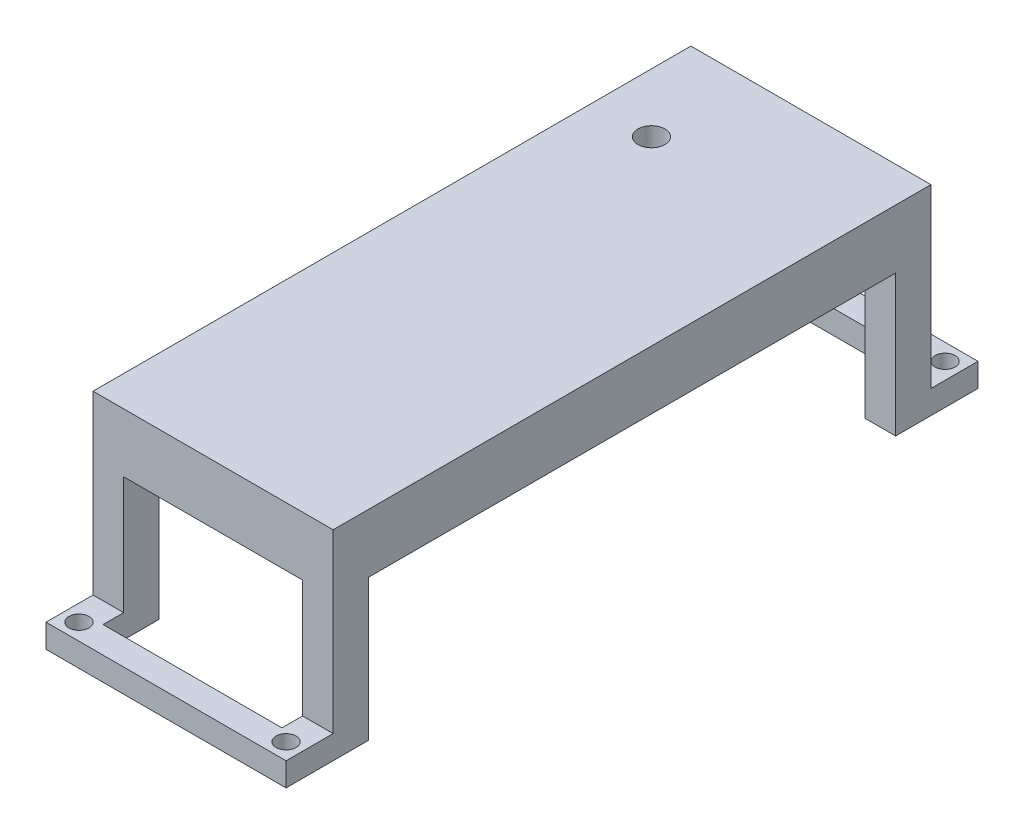
SolidWorks part; units mm, degrees
ref_plane "Front Plane" through (0, 0, 0) normal (0, 0, 1) x (1, 0, 0)
ref_plane "Top Plane" through (0, 0, 0) normal (0, 1, 0) x (1, 0, 0)
ref_plane "Right Plane" through (0, 0, 0) normal (1, 0, 0) x (0, 0, -1)
sketch "Sketch1" plane through (0, 0, 0) normal (0, 1, 0) x (1, 0, 0)
  line L0 (-55, 0) -> (55, 0) construction
  line L1 (-51, 11.25) -> (51, 11.25)
  line L3 (-38, 0) -> (38, 0)
  line L4 (51, 11.25) -> (51, 0)
  line L8 (-51, -13.75) -> (-38, -13.75)
  line L9 (-38, -13.75) -> (-38, 0)
  line L10 (0, -55) -> (0, 55) construction
  line L11 (51, -13.75) -> (38, -13.75)
  line L12 (38, -13.75) -> (38, 0)
  line L13 (51, 0) -> (51, -13.75)
  line L14 (-44, 4.25) -> (-44, 11.25) construction
  line L15 (-44, 4.25) -> (-51, 4.25) construction
  line L19 (-51, 11.25) -> (-51, -13.75)
  circle A0 centre (-44, 4.25) radius 4.25
  circle A1 centre (44, 4.25) radius 4.25
  point P6 (0, 0)
  dimension "D2" = 8.5
  dimension "D1" = 102
  dimension "D3" = 76
  dimension "D4" = 25
  dimension "D5" = 7
extrude "Boss-Extrude1" add sketch "Sketch1" along normal blind 10
sketch "Sketch2" plane through (0, 0, 13.75) normal (0, 0, 1) x (1, 0, 0)
  line L0 (-51, 0) -> (-51, 85)
  line L1 (-51, 10) -> (-51, 0) construction
  line L2 (-51, 85) -> (51, 85)
  line L3 (51, 85) -> (51, 0)
  line L4 (51, 10) -> (51, 0) construction
  line L5 (-51, 0) -> (-38, 0)
  line L6 (-38, 0) -> (-38, 60)
  line L7 (-38, 60) -> (38, 60)
  line L8 (38, 60) -> (38, 0)
  line L9 (-15.9953, 60) -> (-15.9953, 85) construction
  line L10 (-38, 52.4694) -> (-51, 52.4694) construction
  line L11 (13.75, 0) -> (-13.75, 0) construction
  line L12 (38, 0) -> (51, 0)
  line L16 (38, 0) -> (51, 0)
  line L17 (51, 0) -> (51, 10)
  line L18 (51, 10) -> (38, 10)
  line L19 (38, 10) -> (38, 0)
  line L21 (51, 0) -> (51, 10)
  line L23 (38, 10) -> (38, 0)
  dimension "D1" = 60
  dimension "D2" = 25
  dimension "D3" = 0
extrude "Boss-Extrude2" add sketch "Sketch2" against normal blind 5 and the other way blind 10
sketch "Sketch3" plane through (0, 0, 23.75) normal (0, 0, 1) x (1, 0, 0)
  line L0 (51, 85) -> (51, 0) construction
  line L1 (-51, 85) -> (51, 85)
  line L2 (-51, 85) -> (-51, 60)
  line L3 (-51, 60) -> (51, 60)
  line L4 (51, 85) -> (51, 60)
  line L5 (-38, 60) -> (38, 60) construction
extrude "Boss-Extrude3" add sketch "Sketch3" along normal blind 224
sketch "Sketch4" plane through (0, 85, 0) normal (0, 1, 0) x (1, 0, 0)
  line L0 (-51, -8.75) -> (-38, -8.75) construction
  line L1 (-51, -247.75) -> (-51, -8.75) construction
  circle A0 centre (-26, -50.5) radius 5.75
  dimension "D1" = 11.5
  dimension "D2" = 41.75
  dimension "D3" = 25
extrude "Cut-Extrude1" cut sketch "Sketch4" against normal up to next
ref_plane "Plane1" through (0, 0, 135.75) normal (0, 0, -1) x (-1, 0, 0)
mirror "Mirror3" about plane through (0, 0, 135.75) normal (0, 0, -1) of "Boss-Extrude2", "Boss-Extrude1"
mirror "Mirror4" about plane through (0, 0, 135.75) normal (0, 0, -1) of "Boss-Extrude1"
